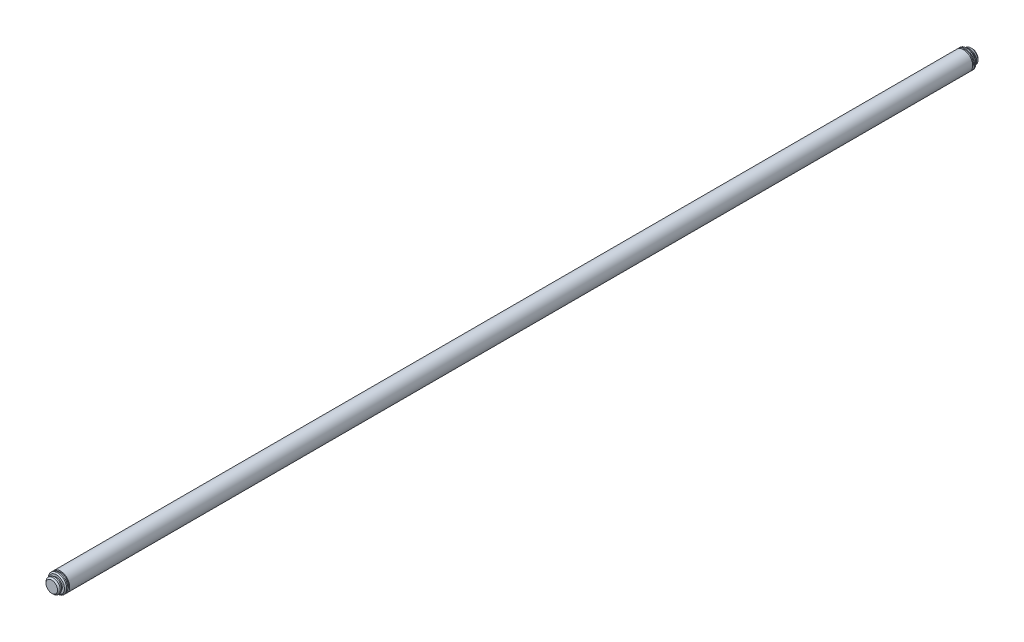
SolidWorks part; units mm, degrees
ref_plane "Plano frontal" through (0, 0, 0) normal (0, 0, 1) x (1, 0, 0)
ref_plane "Plano superior" through (0, 0, 0) normal (0, 1, 0) x (1, 0, 0)
ref_plane "Plano direito" through (0, 0, 0) normal (1, 0, 0) x (0, 0, -1)
sketch "Esboço2" plane through (0, 0, 0) normal (0, 1, 0) x (1, 0, 0)
  line L0 (0, 200) -> (11.6012, 200) construction
  line L1 (0, 0) -> (-2.5, 0)
  line L2 (-4, 2.5) -> (-4, 3)
  line L4 (-4, 3.8) -> (-3.5, 3.8) construction
  line L5 (-4, 3) -> (-3.5, 3) construction
  line L6 (0, 0) -> (0, 400)
  line L8 (-4, 3.8) -> (-4, 396.2)
  line L9 (-4, 2.5) -> (-3.5, 2)
  line L10 (-3.1, 1.2) -> (-3.1, 0.6)
  line L11 (-3.5, 3) -> (-3.5, 3.8)
  line L12 (-4, 3.8) -> (-3.5, 3.8)
  line L13 (-4, 397) -> (-3.5, 397) construction
  line L14 (-3.5, 3) -> (-4, 3)
  line L17 (-3.1, 1.2) -> (-2.6, 1.2)
  line L18 (-3.1, 0.6) -> (-2.5, 0)
  line L19 (-2.6, 2) -> (-2.6, 1.2)
  line L20 (-4, 396.2) -> (-3.5, 396.2) construction
  line L21 (-2.6, 398) -> (-3.5, 398)
  line L22 (-2.6, 398) -> (-2.6, 398.8)
  line L23 (-2.6, 2) -> (-3.5, 2)
  line L24 (-3.1, 399.4) -> (-2.5, 400)
  line L25 (-3.1, 398.8) -> (-2.6, 398.8)
  line L26 (-3.5, 397) -> (-4, 397)
  line L27 (-4, 396.2) -> (-3.5, 396.2)
  line L28 (-3.5, 397) -> (-3.5, 396.2)
  line L29 (-3.1, 398.8) -> (-3.1, 399.4)
  line L30 (-4, 397.5) -> (-3.5, 398)
  line L31 (-4, 397.5) -> (-4, 397)
  line L32 (0, 400) -> (-2.5, 400)
  dimension "D1" = 400
  dimension "D2" = 0.5
  dimension "D3" = 3.8
  dimension "D4" = 0.8
  dimension "D5" = 2.6
  dimension "D6" = 1.2
  dimension "D7" = 3.1
  dimension "D8" = 45
  dimension "D9" = 45
revolve "Revolução1" add sketch "Esboço2" angle 360 about L6
